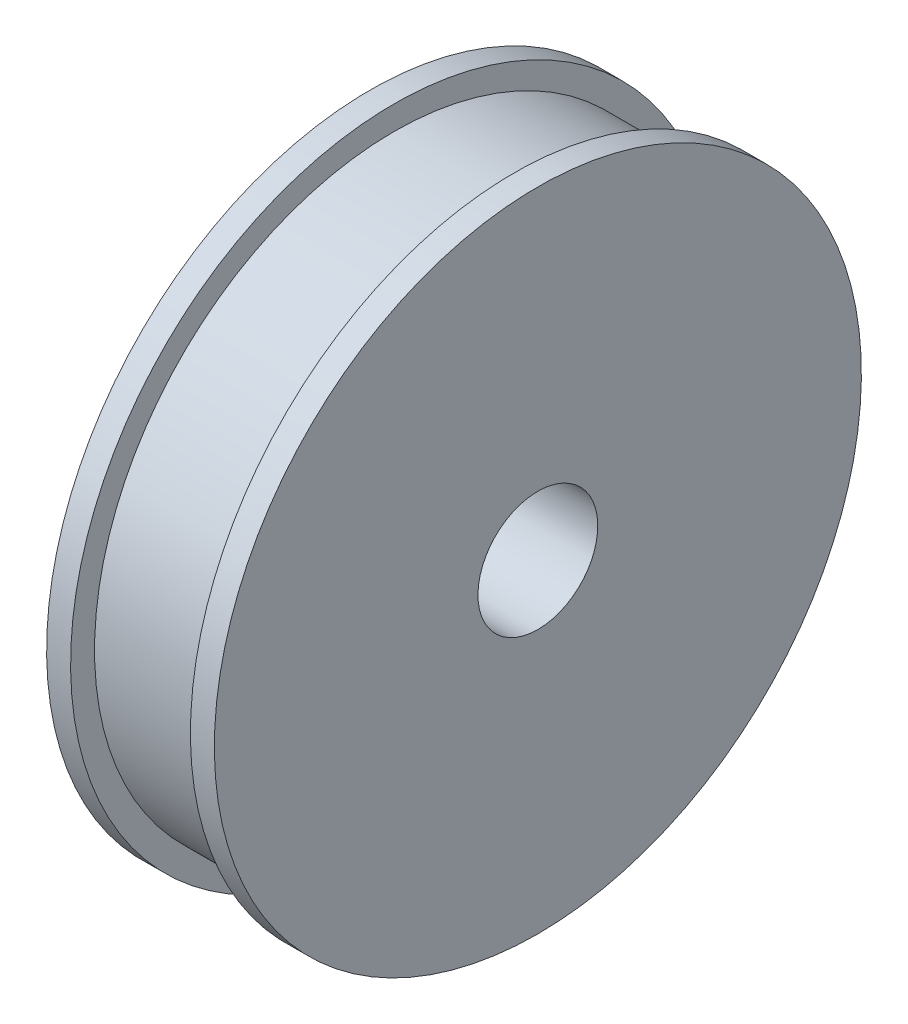
SolidWorks part; units mm, degrees
material "Cast Alloy Steel"
ref_plane "Front Plane" through (0, 0, 0) normal (0, 0, 1) x (1, 0, 0)
ref_plane "Top Plane" through (0, 0, 0) normal (0, 1, 0) x (1, 0, 0)
ref_plane "Right Plane" through (0, 0, 0) normal (1, 0, 0) x (0, 0, -1)
sketch "Sketch1" plane through (0, 0, 0) normal (0, 0, 1) x (1, 0, 0)
  line L0 (-7, 0) -> (7, 0) construction
  line L1 (7, 5) -> (7, 27)
  line L2 (7, 27) -> (5, 27)
  line L3 (5, 27) -> (5, 25)
  line L4 (5, 25) -> (-5, 25)
  line L5 (-5, 25) -> (-5, 27)
  line L6 (-5, 27) -> (-7, 27)
  line L7 (-7, 27) -> (-7, 5)
  line L10 (-7, 5) -> (7, 5)
  point P0 (0, 0)
  point P7 (0, 5)
  dimension "D1" = 5
  dimension "D2" = 2
  dimension "D3" = 10
  dimension "D4" = 27
  dimension "D5" = 25
revolve "Revolve1" add sketch "Sketch1" angle 360 about L0
